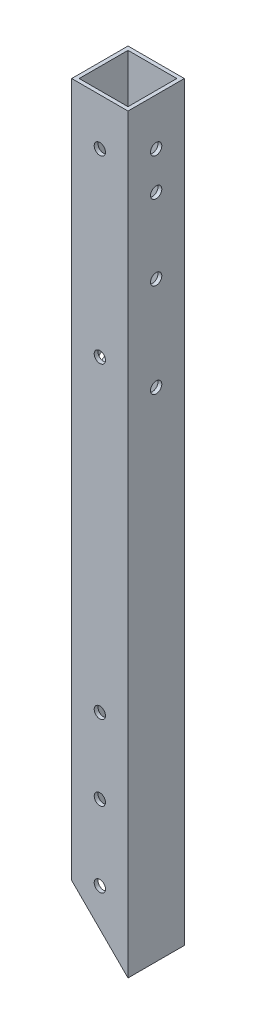
SolidWorks part; units mm, degrees
material "6061-O (SS)"
ref_plane "前视基准面" through (0, 0, 0) normal (0, 0, 1) x (1, 0, 0)
ref_plane "上视基准面" through (0, 0, 0) normal (0, 1, 0) x (1, 0, 0)
ref_plane "右视基准面" through (0, 0, 0) normal (1, 0, 0) x (0, 0, -1)
sketch "草图1" plane through (0, 0, 0) normal (0, 1, 0) x (1, 0, 0)
  line L0 (-6.5, 6.5) -> (6.5, 6.5)
  line L1 (-7.5, -7.5) -> (7.5, -7.5)
  line L2 (-7.5, -7.5) -> (-7.5, 7.5)
  line L3 (-7.5, 7.5) -> (7.5, 7.5)
  line L4 (7.5, -7.5) -> (7.5, 7.5)
  line L5 (-7.5, -7.5) -> (7.5, 7.5) construction
  line L6 (-7.5, 7.5) -> (7.5, -7.5) construction
  line L7 (6.5, -6.5) -> (6.5, 6.5)
  line L8 (-6.5, -6.5) -> (6.5, -6.5)
  line L9 (-6.5, -6.5) -> (-6.5, 6.5)
  point P0 (0, 0)
  dimension "D2" = 15
  dimension "D1" = 1
extrude "凸台-拉伸1" add sketch "草图1" along normal blind 200
sketch "草图2" plane through (0, 0, 7.5) normal (0, 0, 1) x (1, 0, 0)
  line L0 (7.5, 0) -> (-7.5, 0)
  line L1 (-7.5, 0) -> (-7.5, 15)
  line L2 (-7.5, 200) -> (-7.5, 0) construction
  line L3 (-7.5, 15) -> (7.5, 0)
  line L4 (-7.5, 200) -> (7.5, 200) construction
  line L8 (7.5, 200) -> (7.5, 0) construction
  line L9 (0, 7.5) -> (0, 200) construction
  circle A0 centre (0, 37.5) radius 1.5
  circle A1 centre (0, 17.5) radius 1.5
  circle A2 centre (0, 57.5) radius 1.5
  circle A3 centre (0, 187.5) radius 1.5
  circle A4 centre (0, 139.5) radius 1.5
  dimension "D1" = 3
  dimension "D2" = 20
  dimension "D3" = 20
  dimension "D4" = 10
  dimension "D5" = 12.5
  dimension "D6" = 3
  dimension "D7" = 60.5
  dimension "D8" = 3
extrude "切除-拉伸1" cut sketch "草图2" against normal through all
sketch "草图3" plane through (7.5, 0, 0) normal (1, 0, 0) x (0, 0, -1)
  line L0 (0, 200) -> (0, 0) construction
  line L2 (-7.5, 0) -> (7.5, 0) construction
  line L3 (-7.5, 200) -> (7.5, 200) construction
  circle A0 centre (0, 157.5) radius 1.5
  circle A1 centre (0, 177.5) radius 1.5
  circle A2 centre (0, 132.5) radius 1.5
  circle A3 centre (0, 187.5) radius 1.5
  dimension "D1" = 132.5
  dimension "D2" = 25
  dimension "D3" = 20
  dimension "D4" = 3
  dimension "D5" = 10
  dimension "D6" = 3
extrude "切除-拉伸2" cut sketch "草图3" against normal through all
